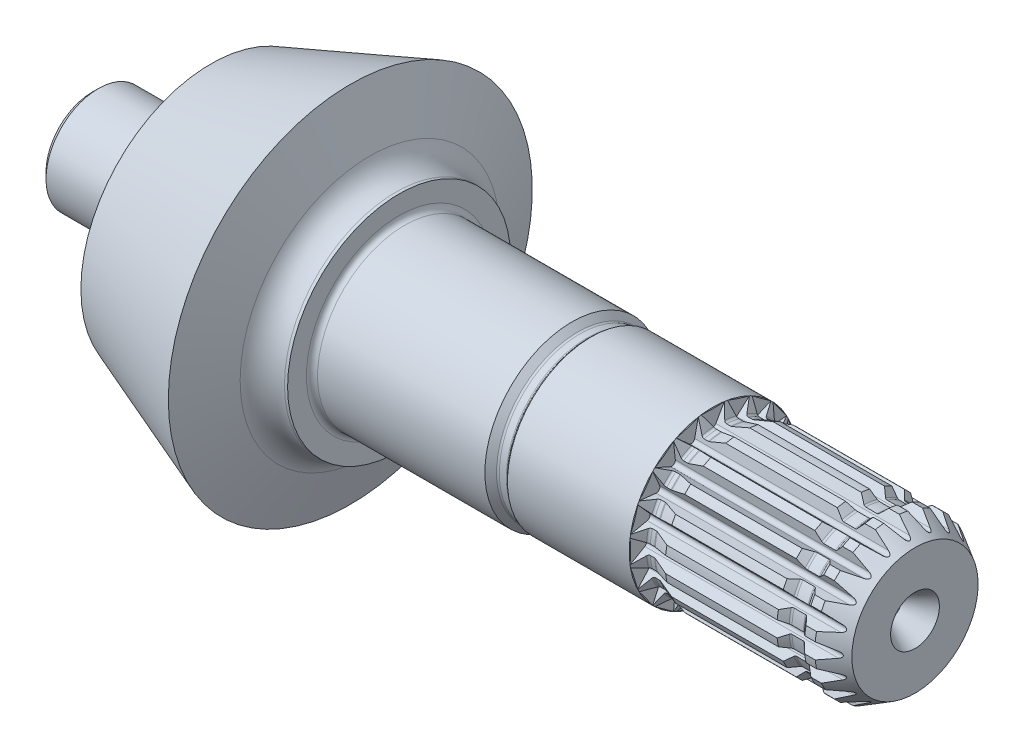
SolidWorks part; units mm, degrees
ref_plane "Plan1" through (0, 0, 0) normal (0, 0, 1) x (1, 0, 0)
ref_plane "Plan2" through (0, 0, 0) normal (0, 1, 0) x (1, 0, 0)
ref_plane "Plan3" through (0, 0, 0) normal (1, 0, 0) x (0, 0, -1)
sketch "Esquisse1" plane through (0, 0, 0) normal (0, 0, 1) x (1, 0, 0)
  line L0 (0, 0) -> (130.2382, 0) construction
  line L1 (-9.2865, 10) -> (7.7135, 10)
  line L2 (7.7135, 10) -> (7.7135, 18.6477)
  line L3 (7.7135, 18.6477) -> (27.7135, 26.1068)
  line L4 (27.7135, 26.1068) -> (30.5123, 18.6022)
  line L5 (34.2602, 16) -> (108.7135, 16)
  line L6 (108.7135, 16) -> (108.7135, 0)
  line L7 (-9.2865, 10) -> (-9.2865, 0)
  line L8 (108.7135, 0) -> (-9.2865, 0)
  line L9 (-42.2865, 0) -> (82.1992, 38.0591) construction
  arc A0 (34.2602, 16) -> (30.5123, 18.6022) centre (34.2602, 20) cw
  point P17 (-42.2865, 0)
  dimension "D1" = 4
  dimension "D2" = 10
  dimension "D3" = 33
  dimension "D4" = 70
  dimension "D5" = 4.5
  dimension "D6" = 50
  dimension "D7" = 16
  dimension "D8" = 151
  dimension "D9" = 17
revolve "ébauche pignon" add sketch "Esquisse1" angle 360 about L0
sketch "profil tournage queue" plane through (0, 0, 0) normal (0, 0, 1) x (1, 0, 0)
  line L0 (34.7135, 20.3517) -> (34.7135, 13.3)
  line L1 (27.7135, 26.1068) -> (27.7135, -26.1068) construction
  line L2 (35.5135, 12.5) -> (59.5135, 12.5)
  line L3 (59.5135, 12.5) -> (60.3472, 11.6663)
  line L4 (60.63, 11.5491) -> (61.63, 11.5491)
  line L5 (61.9085, 11.662) -> (62.257, 12)
  line L6 (62.257, 12) -> (79.7135, 12)
  line L7 (79.7135, 12) -> (80.6176, 10.4341)
  line L8 (80.964, 10.2341) -> (81.5713, 10.2341)
  line L9 (81.7003, 10.2555) -> (83.8856, 11)
  line L10 (83.8856, 11) -> (99.8856, 11)
  line L11 (99.8856, 11) -> (100.7685, 10.1172)
  line L12 (101.0513, 10) -> (102.6813, 10)
  line L13 (102.9642, 10.1172) -> (103.847, 11)
  line L14 (130.2382, 0) -> (54.2599, 0) construction
  line L15 (103.847, 11) -> (105.347, 11)
  line L16 (105.347, 11) -> (111.53, 7.4302)
  line L18 (111.53, 7.4302) -> (114.7135, 7.4302)
  line L19 (114.7135, 7.4302) -> (114.7135, 20.3517)
  line L20 (114.7135, 20.3517) -> (34.7135, 20.3517)
  line L21 (108.7135, 0) -> (-9.2865, 0) construction
  arc A0 (35.5135, 12.5) -> (34.7135, 13.3) centre (35.5135, 13.3) cw
  arc A1 (60.63, 11.5491) -> (60.3472, 11.6663) centre (60.63, 11.9491) cw
  arc A2 (61.9085, 11.662) -> (61.63, 11.5491) centre (61.63, 11.9491) cw
  arc A3 (80.964, 10.2341) -> (80.6176, 10.4341) centre (80.964, 10.6341) cw
  arc A4 (81.7003, 10.2555) -> (81.5713, 10.2341) centre (81.5713, 10.6341) cw
  arc A5 (101.0513, 10) -> (100.7685, 10.1172) centre (101.0513, 10.4) cw
  arc A6 (102.9642, 10.1172) -> (102.6813, 10) centre (102.6813, 10.4) cw
  dimension "D2" = 0.8
  dimension "D3" = 0.4
  dimension "D1" = 7
  dimension "D4" = 12.5
  dimension "D5" = 20.3517
  dimension "D6" = 12
  dimension "D7" = 11
  dimension "D8" = 0.4509
  dimension "D9" = 45
  dimension "D10" = 44.127
  dimension "D11" = 24
  dimension "D12" = 1
  dimension "D13" = 45
  dimension "D14" = 120
  dimension "D15" = 16
  dimension "D16" = 80
  dimension "D17" = 18.814
  dimension "D18" = 0.7659
  dimension "D19" = 0.6074
  dimension "D20" = 1
  dimension "D21" = 11
  dimension "D22" = 30
  dimension "D23" = 7.4302
  dimension "D24" = 1.63
  dimension "D25" = 45
  dimension "D26" = 45
  dimension "D27" = 1.5
revolve "tournage queue" cut sketch "profil tournage queue" angle 360 about L14
sketch "profil avant" plane through (0, 0, 0) normal (0, 0, 1) x (1, 0, 0)
  line L0 (7.2135, 10.5811) -> (7.7135, 11.0811)
  line L1 (108.7135, 0) -> (-9.2865, 0) construction
  line L2 (7.2135, 10.5811) -> (7.2135, 9.5)
  line L3 (6.2135, 8.5) -> (6.0608, 8.5)
  line L4 (6.0608, 8.5) -> (6.0608, 7.5)
  line L5 (6.0608, 7.5) -> (-8.4392, 7.5)
  line L6 (-8.4392, 7.5) -> (-9.9392, 6)
  line L7 (-9.9392, 6) -> (-12.2865, 6)
  line L8 (-12.2865, 6) -> (-12.2865, 22.2746)
  line L9 (-12.2865, 22.2746) -> (7.7135, 22.2746)
  line L10 (7.7135, 18.6477) -> (7.7135, -18.6477) construction
  line L11 (7.7135, 11.0811) -> (7.7135, 22.2746)
  line L12 (2.0571, 0) -> (25.0687, 0) construction
  line L13 (0, 0) -> (130.2382, 0) construction
  arc A0 (7.2135, 9.5) -> (6.2135, 8.5) centre (6.2135, 9.5) cw
  dimension "D2" = 1
  dimension "D1" = 7.5
  dimension "D3" = 14.5
  dimension "D4" = 20
  dimension "D5" = 22.2746
  dimension "D6" = 6
  dimension "D7" = 135
  dimension "D8" = 1.6527
  dimension "D9" = 0.5
  dimension "D10" = 1
  dimension "D11" = 45
  dimension "D12" = 1.0811
revolve "contournage avant pignon" cut sketch "profil avant" angle 360 about L12
sketch "section cannelure" plane through (108.7135, 0, 0) normal (1, 0, 0) x (0, 0, -1)
  line L0 (0, 0) -> (0, 18) construction
  line L1 (0.433, 9.75) -> (1.6579, 11.8715)
  line L2 (-0.433, 9.75) -> (-1.6579, 11.8715)
  line L3 (1.6579, 11.8715) -> (-1.6579, 11.8715)
  arc A1 (0.433, 9.75) -> (-0.433, 9.75) centre (0, 10) cw
  point P9 (0, 9)
  dimension "D1" = 0.5
extrude "cannelure roulée" cut sketch "section cannelure" against normal blind 29
pattern_circular "20 cannelures" count 20 every 18 about axis through (0, 0, 0) along (1, 0, 0)
hole_wizard "Perçage2" positions "Esquisse10" profile "Esquisse9" legacy
sketch "Esquisse10" plane through (-9.2865, 0, 0) normal (-1, 0, 0) x (0, 0, 1)
  point P0 (0, 0)
sketch "Esquisse9" plane through (-9.2865, 0, 0) normal (0, 1, 0) x (0, 0, 1)
  line L0 (0, 0) -> (0, 6.866)
  line L1 (0, 6.866) -> (1.5, 6)
  line L2 (1.5, 6) -> (1.5, 2.5981)
  line L3 (1.5, 2.5981) -> (3, 0)
  line L4 (3, 0) -> (0, 0)
  line L5 (0, -14.3089) -> (0, 102.4216) construction
  line L6 (0, 6.866) -> (-1.5, 6) construction
  line L7 (-1.5, 2.5981) -> (-3, 0) construction
  dimension "Diamètre" = 3
  dimension "Profondeur" = 6
  dimension "Diamètre fraisé" = 6
  dimension "Angle fraisé" = 60
  dimension "Angle" = 120
hole_wizard "Perçage3" positions "Esquisse12" profile "Esquisse11" legacy
sketch "Esquisse12" plane through (108.7135, 0, 0) normal (1, 0, 0) x (0, 0, -1)
  point P0 (0, 0)
sketch "Esquisse11" plane through (108.7135, 0, 0) normal (0, 1, 0) x (0, 0, -1)
  line L0 (0, 0) -> (0, 8.866)
  line L1 (0, 8.866) -> (1.5, 8)
  line L2 (1.5, 8) -> (1.5, 3.4641)
  line L3 (1.5, 3.4641) -> (3.5, 0)
  line L4 (3.5, 0) -> (0, 0)
  line L5 (0, -14.3089) -> (0, 102.4216) construction
  line L6 (0, 8.866) -> (-1.5, 8) construction
  line L7 (-1.5, 3.4641) -> (-3.5, 0) construction
  dimension "Diamètre" = 3
  dimension "Profondeur" = 8
  dimension "Diamètre fraisé" = 7
  dimension "Angle fraisé" = 60
  dimension "Angle" = 120
ref_plane "Plan accrochage fourche" through (124.7135, 0, 0) normal (1, 0, 0) x (0, 0, -1)
